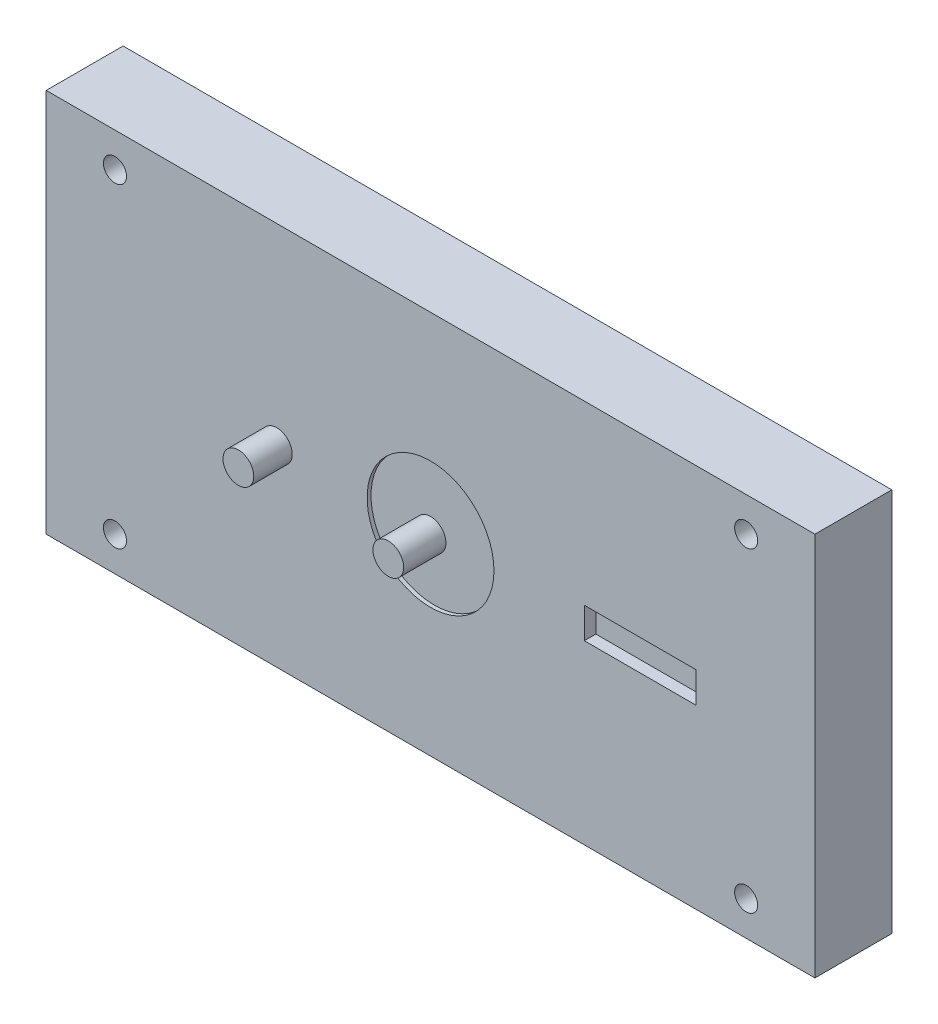
SolidWorks part; units mm, degrees
ref_plane "前视基准面" through (0, 0, 0) normal (0, 0, 1) x (1, 0, 0)
ref_plane "上视基准面" through (0, 0, 0) normal (0, 1, 0) x (1, 0, 0)
ref_plane "右视基准面" through (0, 0, 0) normal (1, 0, 0) x (0, 0, -1)
sketch "草图1" plane through (0, 0, 0) normal (0, 0, 1) x (1, 0, 0)
  line L0 (0, 100) -> (200, 0) construction
  line L1 (0, 0) -> (200, 0)
  line L2 (0, 0) -> (0, 100)
  line L3 (0, 100) -> (200, 100)
  line L4 (200, 0) -> (200, 100)
  line L5 (200, 100) -> (0, 0) construction
  circle A0 centre (100, 50) radius 16.5
extrude "凸台-拉伸1" add sketch "草图1" against normal blind 20 contours L2 L3 L4 L1
sketch "草图2" plane through (0, 0, 0) normal (0, 0, 1) x (1, 0, 0)
  line L0 (0, 100) -> (200, 0) construction
  line L1 (200, 100) -> (0, 0) construction
  circle A0 centre (100, 50) radius 16.5
extrude "切除-拉伸1" cut sketch "草图2" against normal blind 1 contours A0
sketch "草图3" plane through (0, 0, 0) normal (0, 0, 1) x (1, 0, 0)
  line L0 (0, 100) -> (200, 0)
  line L1 (0, 0) -> (200, 100)
  line L2 (100, 50) -> (140, 50)
  line L3 (140, 50) -> (140, 46)
  line L5 (140, 46) -> (169, 46)
  line L6 (140, 46) -> (140, 54)
  line L7 (140, 54) -> (169, 54)
  line L8 (169, 46) -> (169, 54)
extrude "切除-拉伸2" cut sketch "草图3" against normal blind 3 contours L5 L8 L7 L6 L3
sketch "草图4" plane through (0, 0, 0) normal (0, 0, 1) x (1, 0, 0)
  line L0 (0, 100) -> (200, 0) construction
  line L1 (0, 0) -> (200, 100) construction
  line L2 (0, 100) -> (17.8885, 91.0557)
  line L3 (200, 100) -> (182.1115, 91.0557)
  circle A0 centre (17.8885, 91.0557) radius 3
  circle A1 centre (182.1115, 91.0557) radius 3
extrude "切除-拉伸4" cut sketch "草图4" against normal blind 20 contours A0 | A1
sketch "草图5" plane through (0, 0, 0) normal (0, 0, 1) x (1, 0, 0)
  line L0 (0, 0) -> (200, 100) construction
  line L1 (0, 100) -> (200, 0) construction
  line L2 (0, 0) -> (17.8885, 8.9443)
  line L3 (200, 0) -> (182.1115, 8.9443)
  circle A0 centre (17.8885, 8.9443) radius 3
  circle A1 centre (182.1115, 8.9443) radius 3
extrude "切除-拉伸5" cut sketch "草图5" against normal blind 20 contours A1 | A0
sketch "草图6" plane through (0, 0, 0) normal (0, 0, 1) x (1, 0, 0)
  line L0 (0, 100) -> (200, 0)
  line L1 (0, 0) -> (200, 100)
  circle A0 centre (100, 50) radius 4
extrude "凸台-拉伸3" add sketch "草图6" along normal blind 11 separate body contours A0
sketch "草图7" plane through (0, 0, 0) normal (0, 0, 1) x (1, 0, 0)
  line L0 (0, 100) -> (200, 0)
  line L2 (200, 100) -> (0, 0)
  line L3 (100, 50) -> (60, 50)
  circle A1 centre (60, 50) radius 4
extrude "凸台-拉伸4" add sketch "草图7" along normal blind 10 contours A1
